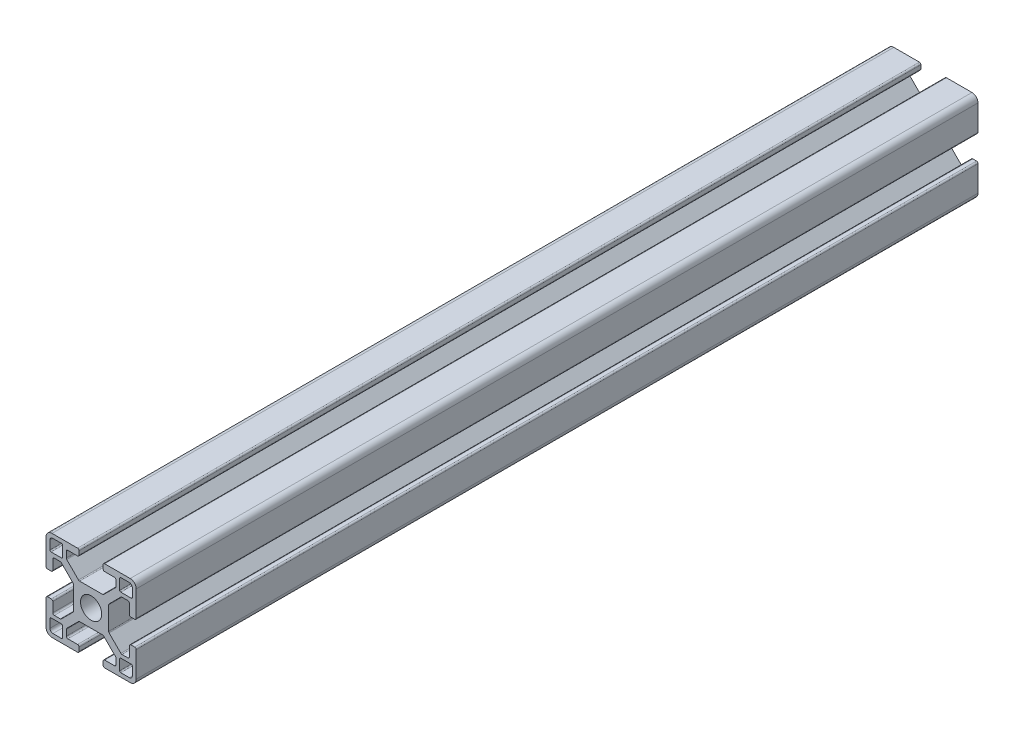
SolidWorks part; units mm, degrees
material "6063-T6"
ref_plane "Front Plane" through (0, 0, 0) normal (0, 0, 1) x (1, 0, 0)
ref_plane "Top Plane" through (0, 0, 0) normal (0, 1, 0) x (1, 0, 0)
ref_plane "Right Plane" through (0, 0, 0) normal (1, 0, 0) x (0, 0, -1)
sketch "Sketch1" plane through (0, 0, 0) normal (0, 0, 1) x (1, 0, 0)
  line L0 (3.9799, -2.4733) -> (3.1981, -1.4942) construction
  line L1 (1.4942, -3.1981) -> (2.4733, -3.9799) construction
  line L2 (-2.4733, -3.9799) -> (-1.4942, -3.1981) construction
  line L3 (-3.1981, -1.4942) -> (-3.9799, -2.4733) construction
  line L4 (-3.9799, 2.4733) -> (-3.1981, 1.4942) construction
  line L5 (-1.4942, 3.1981) -> (-2.4733, 3.9799) construction
  line L6 (2.4733, 3.9799) -> (1.4942, 3.1981) construction
  line L7 (3.1981, 1.4942) -> (3.9799, 2.4733) construction
  line L8 (-12.6999, -13.6999) -> (-9.881, -13.6999)
  line L9 (-13.6999, -9.881) -> (-13.6999, -12.6999)
  line L10 (-9.88, -9.5) -> (-13.3189, -9.5)
  line L11 (-9.5, -13.3189) -> (-9.5, -9.88)
  line L12 (13.6999, -12.6999) -> (13.6999, -9.881)
  line L13 (9.881, -13.6999) -> (12.6999, -13.6999)
  line L14 (9.5, -9.88) -> (9.5, -13.3189)
  line L15 (13.3189, -9.5) -> (9.88, -9.5)
  line L16 (9.88, 9.5) -> (13.3189, 9.5)
  line L17 (9.5, 13.3189) -> (9.5, 9.88)
  line L18 (12.6999, 13.6999) -> (9.881, 13.6999)
  line L19 (13.6999, 9.881) -> (13.6999, 12.6999)
  line L20 (-13.6999, 12.6999) -> (-13.6999, 9.881)
  line L21 (-9.881, 13.6999) -> (-12.6999, 13.6999)
  line L22 (-9.5, 9.88) -> (-9.5, 13.3189)
  line L23 (-13.3189, 9.5) -> (-9.88, 9.5)
  line L24 (14.4999, -4) -> (13.2425, -4)
  line L25 (12.7425, -4.5) -> (12.7425, -7.7325)
  line L26 (12.2428, -8.25) -> (10.2602, -8.25)
  line L27 (9.9066, -8.1035) -> (5.9811, -4.178)
  line L28 (5.8347, -3.8245) -> (5.8347, -1.0125)
  line L29 (5.8347, -1.0125) -> (5.3247, -0.0625) construction
  line L30 (5.3247, -0.0625) -> (5.8347, 0.8875) construction
  line L31 (5.8347, 0.8875) -> (5.8347, 3.8245)
  line L32 (5.9811, 4.178) -> (9.9066, 8.1035)
  line L33 (10.2602, 8.25) -> (12.2428, 8.25)
  line L34 (12.7425, 7.7325) -> (12.7425, 4.5)
  line L35 (13.2425, 4) -> (14.4999, 4)
  line L36 (14.9999, 4.5) -> (14.9999, 12.9999)
  line L37 (12.9999, 14.9999) -> (4.5, 14.9999)
  line L38 (4, 14.4999) -> (4, 13.2425)
  line L39 (4.5, 12.7425) -> (7.7325, 12.7425)
  line L40 (8.25, 12.2428) -> (8.25, 10.2602)
  line L41 (8.1035, 9.9066) -> (4.178, 5.9811)
  line L42 (3.8245, 5.8347) -> (0.95, 5.8347)
  line L43 (0.95, 5.8347) -> (0, 5.3247) construction
  line L44 (0, 5.3247) -> (-0.95, 5.8347) construction
  line L45 (-0.95, 5.8347) -> (-3.8245, 5.8347)
  line L46 (-4.178, 5.9811) -> (-8.1035, 9.9066)
  line L47 (-8.25, 10.2602) -> (-8.25, 12.2428)
  line L48 (-7.7325, 12.7425) -> (-4.5, 12.7425)
  line L49 (-4, 13.2425) -> (-4, 14.4999)
  line L50 (-4.5, 14.9999) -> (-12.9999, 14.9999)
  line L51 (-14.9999, 12.9999) -> (-14.9999, 4.5)
  line L52 (-14.4999, 4) -> (-13.2425, 4)
  line L53 (-12.7425, 4.5) -> (-12.7425, 7.7325)
  line L54 (-12.2428, 8.25) -> (-10.2602, 8.25)
  line L55 (-9.9066, 8.1035) -> (-5.9811, 4.178)
  line L56 (-5.8347, 3.8245) -> (-5.8347, 0.8875)
  line L57 (-5.8347, 0.8875) -> (-5.3247, -0.0625) construction
  line L58 (-5.3247, -0.0625) -> (-5.8347, -1.0125) construction
  line L59 (-5.8347, -1.0125) -> (-5.8347, -3.8245)
  line L60 (-5.9811, -4.178) -> (-9.9066, -8.1035)
  line L61 (-10.2602, -8.25) -> (-12.2428, -8.25)
  line L62 (-12.7425, -7.7325) -> (-12.7425, -4.5)
  line L63 (-13.2425, -4) -> (-14.4999, -4)
  line L64 (-14.9999, -4.5) -> (-14.9999, -12.9999)
  line L65 (-12.9999, -14.9999) -> (-4.5, -14.9999)
  line L66 (-4, -14.4999) -> (-4, -13.2425)
  line L67 (-4.5, -12.7425) -> (-7.7325, -12.7425)
  line L68 (-8.25, -12.2428) -> (-8.25, -10.2602)
  line L69 (-8.1035, -9.9066) -> (-4.178, -5.9811)
  line L70 (-3.8245, -5.8347) -> (-0.95, -5.8347)
  line L71 (-0.95, -5.8347) -> (0, -5.3247) construction
  line L72 (0, -5.3247) -> (0.95, -5.8347) construction
  line L73 (0.95, -5.8347) -> (3.8245, -5.8347)
  line L74 (4.178, -5.9811) -> (8.1035, -9.9066)
  line L75 (8.25, -10.2602) -> (8.25, -12.2428)
  line L76 (7.7325, -12.7425) -> (4.5, -12.7425)
  line L77 (4, -13.2425) -> (4, -14.4999)
  line L78 (4.5, -14.9999) -> (12.9999, -14.9999)
  line L79 (14.9999, -12.9999) -> (14.9999, -4.5)
  line L80 (-5.8347, -1.0125) -> (-5.8347, 0.8875)
  line L81 (-0.95, 5.8347) -> (0.95, 5.8347)
  line L82 (5.8347, 0.8875) -> (5.8347, -1.0125)
  line L83 (-0.95, -5.8347) -> (0.95, -5.8347)
  arc A0 (2.4733, -3.9799) -> (3.9799, -2.4733) centre (3.1422, -3.1422) ccw construction
  arc A1 (-1.4942, -3.1981) -> (1.4942, -3.1981) centre (0, 0) ccw construction
  arc A2 (-3.9799, -2.4733) -> (-2.4733, -3.9799) centre (-3.1422, -3.1422) ccw construction
  arc A3 (-3.1981, 1.4942) -> (-3.1981, -1.4942) centre (0, 0) ccw construction
  arc A4 (-2.4733, 3.9799) -> (-3.9799, 2.4733) centre (-3.1422, 3.1422) ccw construction
  arc A5 (1.4942, 3.1981) -> (-1.4942, 3.1981) centre (0, 0) ccw construction
  arc A6 (3.9799, 2.4733) -> (2.4733, 3.9799) centre (3.1422, 3.1422) ccw construction
  arc A7 (3.1981, -1.4942) -> (3.1981, 1.4942) centre (0, 0) ccw construction
  arc A8 (-13.6999, -12.6999) -> (-12.6999, -13.6999) centre (-12.6999, -12.6999) ccw
  arc A9 (-13.3189, -9.5) -> (-13.6999, -9.881) centre (-13.3189, -9.881) ccw
  arc A10 (-9.5, -9.88) -> (-9.88, -9.5) centre (-9.88, -9.88) ccw
  arc A11 (-9.881, -13.6999) -> (-9.5, -13.3189) centre (-9.881, -13.3189) ccw
  arc A12 (12.6999, -13.6999) -> (13.6999, -12.6999) centre (12.6999, -12.6999) ccw
  arc A13 (9.5, -13.3189) -> (9.881, -13.6999) centre (9.881, -13.3189) ccw
  arc A14 (9.88, -9.5) -> (9.5, -9.88) centre (9.88, -9.88) ccw
  arc A15 (13.6999, -9.881) -> (13.3189, -9.5) centre (13.3189, -9.881) ccw
  arc A16 (9.5, 9.88) -> (9.88, 9.5) centre (9.88, 9.88) ccw
  arc A17 (9.881, 13.6999) -> (9.5, 13.3189) centre (9.881, 13.3189) ccw
  arc A18 (13.6999, 12.6999) -> (12.6999, 13.6999) centre (12.6999, 12.6999) ccw
  arc A19 (13.3189, 9.5) -> (13.6999, 9.881) centre (13.3189, 9.881) ccw
  arc A20 (14.9999, -4.5) -> (14.4999, -4) centre (14.4999, -4.5) ccw
  arc A21 (13.2425, -4) -> (12.7425, -4.5) centre (13.2425, -4.5) ccw
  arc A22 (12.2428, -8.25) -> (12.7425, -7.7325) centre (12.2428, -7.75) ccw
  arc A23 (9.9066, -8.1035) -> (10.2602, -8.25) centre (10.2602, -7.75) ccw
  arc A24 (5.8347, -3.8245) -> (5.9811, -4.178) centre (6.3347, -3.8245) ccw
  arc A25 (5.9811, 4.178) -> (5.8347, 3.8245) centre (6.3347, 3.8245) ccw
  arc A26 (10.2602, 8.25) -> (9.9066, 8.1035) centre (10.2602, 7.75) ccw
  arc A27 (12.7425, 7.7325) -> (12.2428, 8.25) centre (12.2428, 7.75) ccw
  arc A28 (12.7425, 4.5) -> (13.2425, 4) centre (13.2425, 4.5) ccw
  arc A29 (14.4999, 4) -> (14.9999, 4.5) centre (14.4999, 4.5) ccw
  arc A30 (14.9999, 12.9999) -> (12.9999, 14.9999) centre (12.9999, 12.9999) ccw
  arc A31 (4.5, 14.9999) -> (4, 14.4999) centre (4.5, 14.4999) ccw
  arc A32 (4, 13.2425) -> (4.5, 12.7425) centre (4.5, 13.2425) ccw
  arc A33 (8.25, 12.2428) -> (7.7325, 12.7425) centre (7.75, 12.2428) ccw
  arc A34 (8.1035, 9.9066) -> (8.25, 10.2602) centre (7.75, 10.2602) ccw
  arc A35 (3.8245, 5.8347) -> (4.178, 5.9811) centre (3.8245, 6.3347) ccw
  arc A36 (-4.178, 5.9811) -> (-3.8245, 5.8347) centre (-3.8245, 6.3347) ccw
  arc A37 (-8.25, 10.2602) -> (-8.1035, 9.9066) centre (-7.75, 10.2602) ccw
  arc A38 (-7.7325, 12.7425) -> (-8.25, 12.2428) centre (-7.75, 12.2428) ccw
  arc A39 (-4.5, 12.7425) -> (-4, 13.2425) centre (-4.5, 13.2425) ccw
  arc A40 (-4, 14.4999) -> (-4.5, 14.9999) centre (-4.5, 14.4999) ccw
  arc A41 (-12.9999, 14.9999) -> (-14.9999, 12.9999) centre (-12.9999, 12.9999) ccw
  arc A42 (-14.9999, 4.5) -> (-14.4999, 4) centre (-14.4999, 4.5) ccw
  arc A43 (-13.2425, 4) -> (-12.7425, 4.5) centre (-13.2425, 4.5) ccw
  arc A44 (-12.2428, 8.25) -> (-12.7425, 7.7325) centre (-12.2428, 7.75) ccw
  arc A45 (-9.9066, 8.1035) -> (-10.2602, 8.25) centre (-10.2602, 7.75) ccw
  arc A46 (-5.8347, 3.8245) -> (-5.9811, 4.178) centre (-6.3347, 3.8245) ccw
  arc A47 (-5.9811, -4.178) -> (-5.8347, -3.8245) centre (-6.3347, -3.8245) ccw
  arc A48 (-10.2602, -8.25) -> (-9.9066, -8.1035) centre (-10.2602, -7.75) ccw
  arc A49 (-12.7425, -7.7325) -> (-12.2428, -8.25) centre (-12.2428, -7.75) ccw
  arc A50 (-12.7425, -4.5) -> (-13.2425, -4) centre (-13.2425, -4.5) ccw
  arc A51 (-14.4999, -4) -> (-14.9999, -4.5) centre (-14.4999, -4.5) ccw
  arc A52 (-14.9999, -12.9999) -> (-12.9999, -14.9999) centre (-12.9999, -12.9999) ccw
  arc A53 (-4.5, -14.9999) -> (-4, -14.4999) centre (-4.5, -14.4999) ccw
  arc A54 (-4, -13.2425) -> (-4.5, -12.7425) centre (-4.5, -13.2425) ccw
  arc A55 (-8.25, -12.2428) -> (-7.7325, -12.7425) centre (-7.75, -12.2428) ccw
  arc A56 (-8.1035, -9.9066) -> (-8.25, -10.2602) centre (-7.75, -10.2602) ccw
  arc A57 (-3.8245, -5.8347) -> (-4.178, -5.9811) centre (-3.8245, -6.3347) ccw
  arc A58 (4.178, -5.9811) -> (3.8245, -5.8347) centre (3.8245, -6.3347) ccw
  arc A59 (8.25, -10.2602) -> (8.1035, -9.9066) centre (7.75, -10.2602) ccw
  arc A60 (7.7325, -12.7425) -> (8.25, -12.2428) centre (7.75, -12.2428) ccw
  arc A61 (4.5, -12.7425) -> (4, -13.2425) centre (4.5, -13.2425) ccw
  arc A62 (4, -14.4999) -> (4.5, -14.9999) centre (4.5, -14.4999) ccw
  arc A63 (12.9999, -14.9999) -> (14.9999, -12.9999) centre (12.9999, -12.9999) ccw
  arc A64 (-12.6999, 13.6999) -> (-13.6999, 12.6999) centre (-12.6999, 12.6999) ccw
  arc A65 (-9.5, 13.3189) -> (-9.881, 13.6999) centre (-9.881, 13.3189) ccw
  arc A66 (-9.88, 9.5) -> (-9.5, 9.88) centre (-9.88, 9.88) ccw
  arc A67 (-13.6999, 9.881) -> (-13.3189, 9.5) centre (-13.3189, 9.881) ccw
  circle A68 centre (0, 0) radius 3.53
extrude "Boss-Extrude1" add sketch "Sketch1" along normal mid plane 280
sketch "Sketch2" plane through (-14.9999, 0, 0) normal (-1, 0, 0) x (0, 0, 1)
  line L0 (-140, 3.8245) -> (-140, -3.8245) construction
  circle A0 centre (-135, 0) radius 2.5
  circle A1 centre (-100, 0) radius 2.5
  point P6 (-140, 0)
  dimension "D1" = 35
  dimension "D2" = 5
extrude "Cut-Extrude1" cut sketch "Sketch2" against normal blind 27
